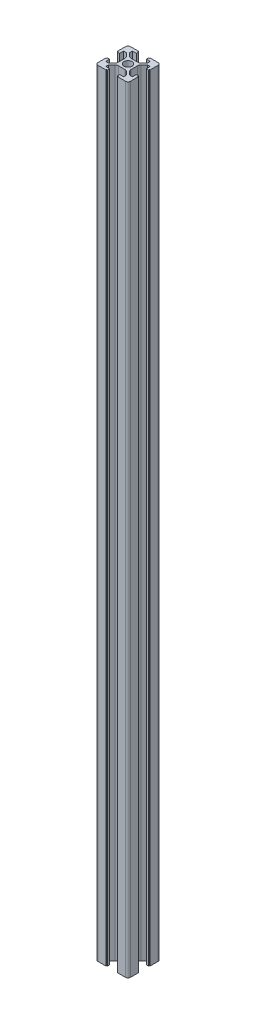
SolidWorks part; units mm, degrees
ref_plane "Front Plane" through (0, 0, 0) normal (0, 0, 1) x (1, 0, 0)
ref_plane "Top Plane" through (0, 0, 0) normal (0, 1, 0) x (1, 0, 0)
ref_plane "Right Plane" through (0, 0, 0) normal (1, 0, 0) x (0, 0, -1)
sketch "Sketch1" plane through (0, 0, 0) normal (0, 1, 0) x (1, 0, 0)
  line L17 (-14.0001, -7.2463) -> (-15.3001, -7.2463)
  line L18 (-15.3001, -7.2463) -> (-15.3001, -7.7463)
  line L71 (-15.3001, -7.7463) -> (-15.8001, -7.7463)
  line L92 (-15.8001, -7.7463) -> (-15.8001, -12.6463)
  line L93 (-14.3001, -14.1463) -> (-9.4001, -14.1463)
  line L94 (-9.4001, -14.1463) -> (-9.4001, -13.6463)
  line L95 (-9.4001, -13.6463) -> (-8.9001, -13.6463)
  line L96 (-8.9001, -13.6463) -> (-8.9001, -12.3463)
  line L97 (-8.9001, -12.3463) -> (-11.3001, -12.3463)
  line L98 (-11.3001, -12.3463) -> (-11.3001, -10.707)
  line L99 (-11.3001, -10.707) -> (-9.2253, -8.6321)
  line L100 (-7.811, -8.0463) -> (-3.7892, -8.0463)
  line L101 (-2.375, -8.6321) -> (-0.3001, -10.707)
  line L102 (-0.3001, -10.707) -> (-0.3001, -12.3463)
  line L103 (-0.3001, -12.3463) -> (-2.7001, -12.3463)
  line L104 (-2.7001, -12.3463) -> (-2.7001, -13.6463)
  line L105 (-2.7001, -13.6463) -> (-2.2001, -13.6463)
  line L106 (-2.2001, -13.6463) -> (-2.2001, -14.1463)
  line L107 (-2.2001, -14.1463) -> (2.6999, -14.1463)
  line L108 (4.1999, -12.6463) -> (4.1999, -7.7463)
  line L109 (4.1999, -7.7463) -> (3.6999, -7.7463)
  line L110 (3.6999, -7.7463) -> (3.6999, -7.2463)
  line L111 (3.6999, -7.2463) -> (2.3999, -7.2463)
  line L112 (2.3999, -7.2463) -> (2.3999, -9.6463)
  line L113 (2.3999, -9.6463) -> (0.7605, -9.6463)
  line L114 (0.7605, -9.6463) -> (-1.3143, -7.5715)
  line L115 (-1.9001, -6.1572) -> (-1.9001, -2.1354)
  line L116 (-1.3143, -0.7212) -> (0.7605, 1.3537)
  line L117 (0.7605, 1.3537) -> (2.3999, 1.3537)
  line L118 (2.3999, 1.3537) -> (2.3999, -1.0463)
  line L119 (2.3999, -1.0463) -> (3.6999, -1.0463)
  line L120 (3.6999, -1.0463) -> (3.6999, -0.5463)
  line L121 (3.6999, -0.5463) -> (4.1999, -0.5463)
  line L122 (4.1999, -0.5463) -> (4.1999, 4.3537)
  line L123 (2.6999, 5.8537) -> (-2.2001, 5.8537)
  line L124 (-2.2001, 5.8537) -> (-2.2001, 5.3537)
  line L125 (-2.2001, 5.3537) -> (-2.7001, 5.3537)
  line L126 (-2.7001, 5.3537) -> (-2.7001, 4.0537)
  line L127 (-2.7001, 4.0537) -> (-0.3001, 4.0537)
  line L128 (-0.3001, 4.0537) -> (-0.3001, 2.4143)
  line L129 (-0.3001, 2.4143) -> (-2.375, 0.3395)
  line L130 (-3.7892, -0.2463) -> (-7.811, -0.2463)
  line L131 (-9.2253, 0.3395) -> (-11.3001, 2.4143)
  line L132 (-11.3001, 2.4143) -> (-11.3001, 4.0537)
  line L133 (-11.3001, 4.0537) -> (-8.9001, 4.0537)
  line L134 (-8.9001, 4.0537) -> (-8.9001, 5.3537)
  line L135 (-8.9001, 5.3537) -> (-9.4001, 5.3537)
  line L136 (-9.4001, 5.3537) -> (-9.4001, 5.8537)
  line L137 (-9.4001, 5.8537) -> (-14.3001, 5.8537)
  line L138 (-15.8001, 4.3537) -> (-15.8001, -0.5463)
  line L139 (-15.8001, -0.5463) -> (-15.3001, -0.5463)
  line L140 (-15.3001, -0.5463) -> (-15.3001, -1.0463)
  line L141 (-15.3001, -1.0463) -> (-14.0001, -1.0463)
  line L142 (-14.0001, -1.0463) -> (-14.0001, 1.3537)
  line L143 (-14.0001, 1.3537) -> (-12.3608, 1.3537)
  line L144 (-12.3608, 1.3537) -> (-10.2859, -0.7212)
  line L145 (-9.7001, -2.1354) -> (-9.7001, -6.1572)
  line L146 (-10.2859, -7.5715) -> (-12.3608, -9.6463)
  line L147 (-12.3608, -9.6463) -> (-14.0001, -9.6463)
  line L148 (-14.0001, -9.6463) -> (-14.0001, -7.2463)
  arc A2 (-15.8001, -12.6463) -> (-14.3001, -14.1463) centre (-14.3001, -12.6463) ccw
  arc A3 (-9.2253, -8.6321) -> (-7.811, -8.0463) centre (-7.811, -10.0463) cw
  arc A4 (-3.7892, -8.0463) -> (-2.375, -8.6321) centre (-3.7892, -10.0463) cw
  arc A5 (2.6999, -14.1463) -> (4.1999, -12.6463) centre (2.6999, -12.6463) ccw
  arc A6 (-1.3143, -7.5715) -> (-1.9001, -6.1572) centre (0.0999, -6.1572) cw
  arc A7 (-1.9001, -2.1354) -> (-1.3143, -0.7212) centre (0.0999, -2.1354) cw
  arc A8 (4.1999, 4.3537) -> (2.6999, 5.8537) centre (2.6999, 4.3537) ccw
  arc A9 (-2.375, 0.3395) -> (-3.7892, -0.2463) centre (-3.7892, 1.7537) cw
  arc A10 (-7.811, -0.2463) -> (-9.2253, 0.3395) centre (-7.811, 1.7537) cw
  arc A11 (-14.3001, 5.8537) -> (-15.8001, 4.3537) centre (-14.3001, 4.3537) ccw
  arc A12 (-10.2859, -0.7212) -> (-9.7001, -2.1354) centre (-11.7001, -2.1354) cw
  arc A13 (-9.7001, -6.1572) -> (-10.2859, -7.5715) centre (-11.7001, -6.1572) cw
  circle A14 centre (-5.8001, -4.1463) radius 2.5
  point P92 (-22.434, -0.7455)
  dimension "D2" = 5
  dimension "D5" = 1.8
  dimension "D9" = 1.5
  dimension "D1" = 7.8
  dimension "D3" = 7.8
  dimension "D4" = 1.3
  dimension "D6" = 0.5
  dimension "D7" = 4.5
  dimension "D8" = 4.5
  dimension "D10" = 1.8
  dimension "D11" = 1.3
  dimension "D12" = 0.5
  dimension "D13" = 4.3
  dimension "D14" = 1.6
extrude "Boss-Extrude1" add sketch "Sketch1" along normal blind 478.02
